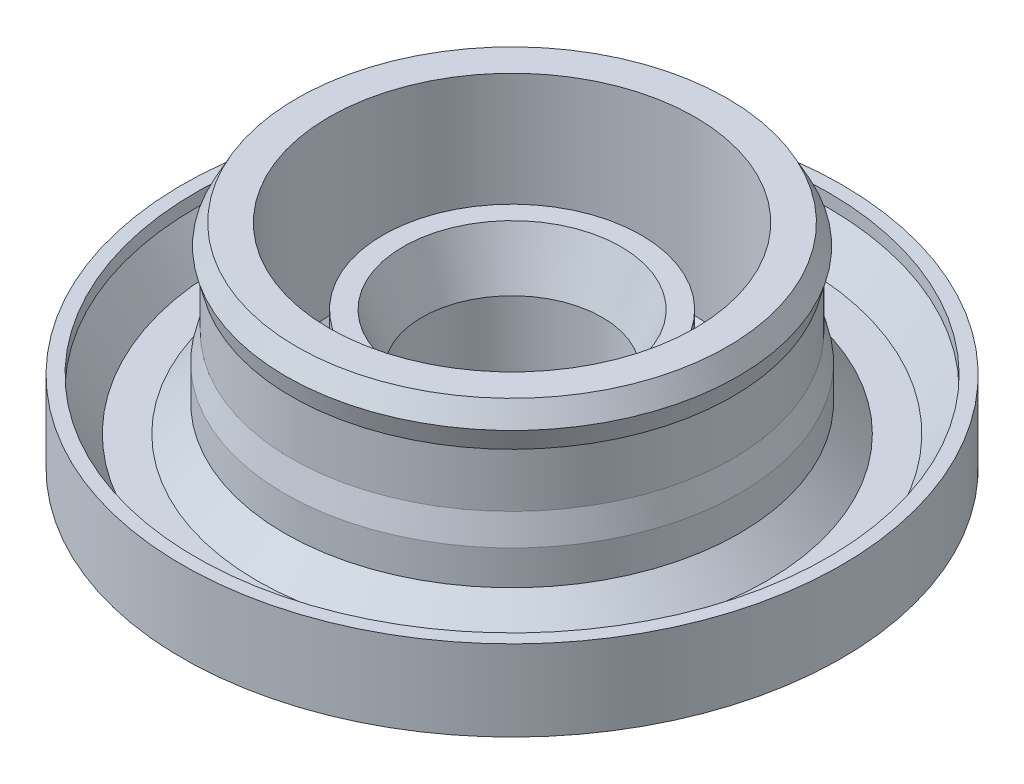
SolidWorks part; units mm, degrees
material "PET"
ref_plane "Front Plane" through (0, 0, 0) normal (0, 0, 1) x (1, 0, 0)
ref_plane "Top Plane" through (0, 0, 0) normal (0, 1, 0) x (1, 0, 0)
ref_plane "Right Plane" through (0, 0, 0) normal (1, 0, 0) x (0, 0, -1)
sketch "Sketch1" plane through (0, 0, 0) normal (0, 0, 1) x (1, 0, 0)
  line L0 (0, 0) -> (0, 14.1139) construction
  line L1 (-12.25, 7.1) -> (-4.45, 7.1)
  line L2 (-4.45, 7.1) -> (-4.45, 0)
  line L3 (-4.45, 0) -> (-6, 0)
  line L4 (-6, 0) -> (-6, 4.1)
  line L5 (-6, 4.1) -> (-12.25, 4.1)
  line L6 (-12.25, 4.1) -> (-12.25, 7.1)
  dimension "D1" = 6
  dimension "D2" = 4.45
  dimension "D3" = 12.25
  dimension "D4" = 4.1
  dimension "D5" = 3
revolve "Revolve1" add sketch "Sketch1" angle 360 about L0
sketch "Sketch2" plane through (0, 0, 0) normal (0, 0, 1) x (1, 0, 0)
  line L0 (-12.25, 7.1) -> (-4.45, 7.1)
  line L1 (4.45, 7.1) -> (12.25, 7.1)
  line L2 (-11.75, 7.1) -> (-11.75, 6.6)
  line L3 (-12.25, 7.1) -> (-4.45, 7.1) construction
  line L4 (-4.45, 7.1) -> (-4.45, 0)
  line L5 (4.45, 0) -> (4.45, 7.1)
  line L6 (-11.75, 6.6) -> (-10.7697, 5.2)
  line L7 (-4.45, 7.1) -> (-4.45, 0) construction
  line L8 (-10.7697, 5.2) -> (-6.8, 5.2)
  line L9 (-6.8, 5.2) -> (-6.8, 4.8)
  line L10 (-6.8, 4.8) -> (0, 4.8)
  line L11 (0, 4.8) -> (0, 10.7782)
  line L12 (0, 10.7782) -> (-11.75, 10.7782)
  line L13 (-11.75, 10.7782) -> (-11.75, 7.1)
  line L14 (-12.25, 4.1) -> (12.25, 4.1) construction
  dimension "D1" = 0.5
  dimension "D2" = 0.5
  dimension "D3" = 35
  dimension "D4" = 1.1
  dimension "D5" = 0.7
  dimension "D6" = 6.8
revolve "Cut-Revolve1" cut sketch "Sketch2" angle 360 about L11
sketch "Sketch3" plane through (0, 0, 0) normal (0, 0, 1) x (1, 0, 0)
  line L0 (-4.8, 9.2) -> (-4.8, 4.1)
  line L1 (-4.8, 4.1) -> (-3.35, 4.1)
  line L2 (-3.35, 4.1) -> (-3.35, 7.2768)
  line L3 (-3.35, 7.2768) -> (-4.05, 9.2)
  line L4 (-4.05, 9.2) -> (-4.8, 9.2)
  line L5 (0, 0) -> (0, 9.5497) construction
  line L6 (6.8, 4.8) -> (-6.8, 4.8) construction
  line L7 (-6, 4.1) -> (6, 4.1) construction
  point P10 (-4.8, 4.1)
  dimension "D1" = 0.75
  dimension "D2" = 4.8
  dimension "D3" = 3.35
  dimension "D4" = 4.4
  dimension "D5" = 20
revolve "Revolve2" add sketch "Sketch3" angle 360 about L5
sketch "Sketch4" plane through (0, 4.1, 0) normal (0, -1, 0) x (1, 0, 0)
  circle A0 centre (0, 0) radius 3.85
  circle A1 centre (0, 0) radius 3.35
  circle A2 centre (0, 0) radius 3.35
  dimension "D1" = 7.7
extrude "Boss-Extrude1" add sketch "Sketch4" along normal blind 2.1
sketch "Sketch5" plane through (0, 0, 0) normal (0, 0, 1) x (1, 0, 0)
  line L0 (0, 0) -> (0, 19.3929) construction
  line L1 (-6.8, 12) -> (-6.8, 5.2)
  line L2 (-6.8, 5.2) -> (-9.4697, 5.2)
  line L3 (-9.4697, 5.2) -> (-8.45, 6.2197)
  line L4 (-8.45, 6.2197) -> (-8.45, 7.5)
  line L5 (-8.45, 7.5) -> (-8.2, 8.5)
  line L6 (-8.2, 8.5) -> (-8.2, 10.5)
  line L7 (-8.2, 10.5) -> (-8.4, 11.2464)
  line L8 (-8.4, 11.2464) -> (-8, 12)
  line L9 (-8, 12) -> (-6.8, 12)
  line L10 (10.7697, 5.2) -> (-10.7697, 5.2) construction
  line L11 (6.8, 5.2) -> (-6.8, 5.2) construction
  line L12 (11.75, 6.6) -> (10.7697, 5.2)
  line L13 (-10.7697, 5.2) -> (-11.75, 6.6)
  line L14 (-10.7697, 5.2) -> (-11.75, 6.6) construction
  line L15 (11.75, 6.6) -> (10.7697, 5.2)
  point P3 (-9.9524, 5.2)
  point P15 (-6.8, 5.2)
  point P18 (-8.45, 10.9549)
  point P19 (-7.9882, 10.5)
  point P20 (-8.45, 7.9456)
  dimension "D1" = 6.8
  dimension "D2" = 45
  dimension "D3" = 8.45
  dimension "D4" = 1.5
  dimension "D5" = 12
  dimension "D6" = 2
  dimension "D7" = 15
  dimension "D8" = 1.2
  dimension "D9" = 8.2
  dimension "D10" = 8.4
  dimension "D11" = 1
  dimension "D12" = 1.3
revolve "Revolve3" add sketch "Sketch5" angle 360 about L0
sketch "Sketch6" plane through (0, 0, 0) normal (0, 0, 1) x (1, 0, 0)
  line L0 (6.8, 4.8) -> (4.8, 4.8)
  line L1 (-4.8, 4.8) -> (-6.8, 4.8)
  line L2 (-4.8, 4.8) -> (-6.8, 4.8) construction
  line L3 (-6.8, 5.6) -> (-6, 4.8)
  line L4 (-6.8, 4.8) -> (-6.8, 12)
  line L5 (6.8, 12) -> (6.8, 4.8)
  line L6 (-6, 4.8) -> (-6, 4.5438)
  line L7 (-6.8, 4.8) -> (-6.8, 12) construction
  line L8 (-6, 4.5438) -> (-7.1751, 4.5438)
  line L9 (-7.1751, 4.5438) -> (-7.1751, 5.6)
  line L11 (-7.1751, 5.6) -> (-6.8, 5.6)
  line L13 (-12.25, 4.1) -> (12.25, 4.1) construction
  line L14 (0, 0) -> (0, 10.7026) construction
  point P8 (-6.9875, 5.6)
  dimension "D1" = 1.5
  dimension "D2" = 6
revolve "Revolve4" add sketch "Sketch6" angle 360 about L14
fillet "Fillet1" radius 0.5 1 edges at (0, 0, -6)
fillet "Fillet2" radius 0.2 1 edges at (0, 2, -3.85)
